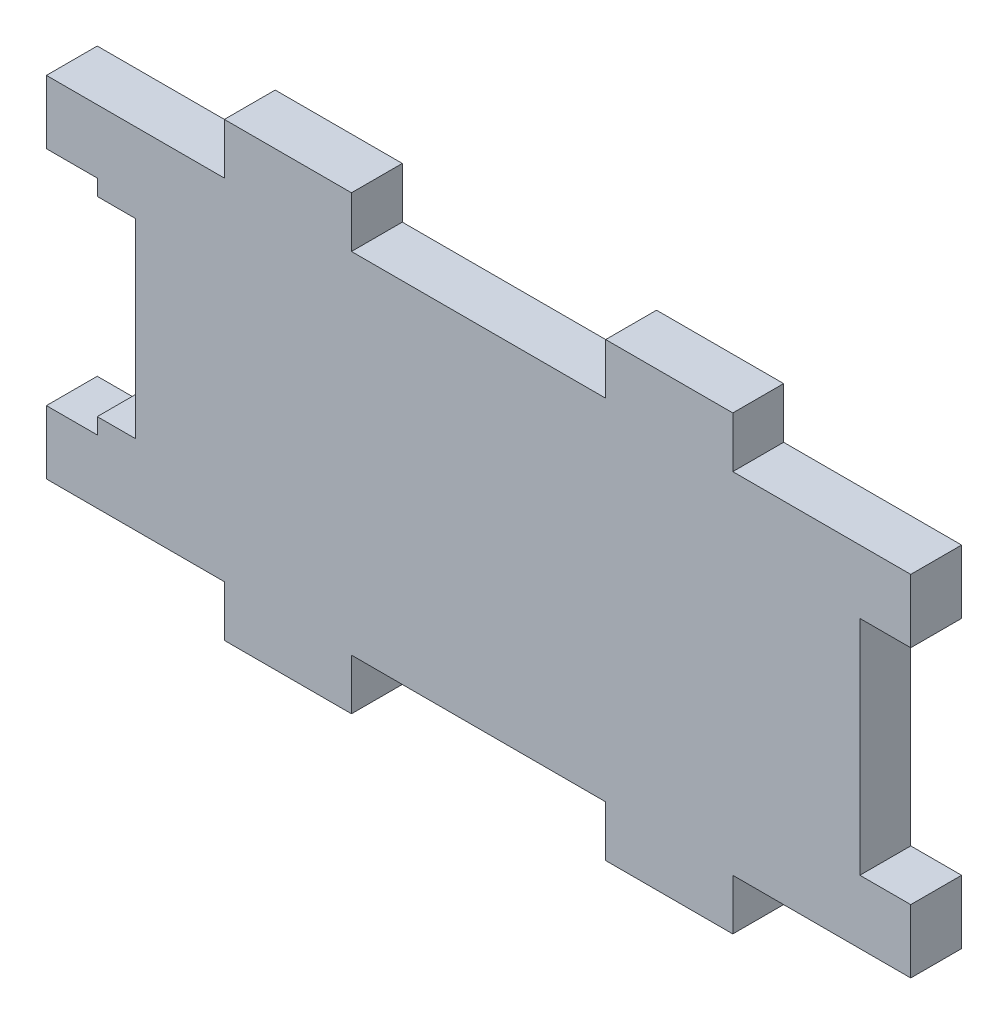
SolidWorks part; units mm, degrees
ref_plane "Front Plane" through (0, 0, 0) normal (0, 0, 1) x (1, 0, 0)
ref_plane "Top Plane" through (0, 0, 0) normal (0, 1, 0) x (1, 0, 0)
ref_plane "Right Plane" through (0, 0, 0) normal (1, 0, 0) x (0, 0, -1)
sketch "Sketch1" plane through (0, 0, 0) normal (0, 0, 1) x (1, 0, 0)
  line L1 (-60, 27.5) -> (60, 27.5)
  line L2 (-60, 27.5) -> (-60, -27.5)
  line L3 (-60, -27.5) -> (60, -27.5)
  line L4 (60, 27.5) -> (60, -27.5)
  point P4 (0, 27.5)
  point P6 (60, 0)
  dimension "D1" = 55
  dimension "D2" = 120
extrude "Boss-Extrude1" add sketch "Sketch1" along normal blind 8
sketch "Sketch2" plane through (0, 0, 8) normal (0, 0, 1) x (1, 0, 0)
  line L0 (-60, 27.5) -> (-60, -27.5) construction
  line L1 (-92.7508, 15) -> (-54, 15)
  line L2 (-92.7508, 15) -> (-92.7508, -15)
  line L3 (-92.7508, -15) -> (-54, -15)
  line L4 (-54, 15) -> (-54, -15)
  point P4 (-54, 0)
  point P7 (-60, 0)
  dimension "D1" = 30
  dimension "D2" = 6
extrude "Cut-Extrude1" cut sketch "Sketch2" against normal up to next
sketch "Sketch4" plane through (60, 0, 0) normal (1, 0, 0) x (0, 0, -1)
  line L1 (-8, 27.5) -> (0, 27.5)
  line L2 (-8, 27.5) -> (-8, 17.5)
  line L3 (-8, 17.5) -> (0, 17.5)
  line L4 (0, 27.5) -> (0, 17.5)
  line L5 (-8, 27.5) -> (0, 27.5) construction
  line L6 (0, -27.5) -> (0, 27.5) construction
  line L7 (-23.1797, 0) -> (12.6777, 0) construction
  line L8 (-8, -27.5) -> (-8, -17.5)
  line L9 (-8, -27.5) -> (0, -27.5)
  line L10 (0, -27.5) -> (0, -17.5)
  line L11 (-8, -17.5) -> (0, -17.5)
  dimension "D1" = 10
extrude "Boss-Extrude3" add sketch "Sketch4" along normal blind 8
sketch "Sketch6" plane through (0, -27.5, 0) normal (0, -1, 0) x (1, 0, 0)
  line L0 (0, 25.2996) -> (0, -15.5638) construction
  line L1 (-40, 8) -> (-20, 8)
  line L2 (-40, 8) -> (-40, 0)
  line L3 (-40, 0) -> (-20, 0)
  line L4 (-20, 8) -> (-20, 0)
  line L5 (20, 8) -> (20, 0)
  line L6 (40, 0) -> (20, 0)
  line L7 (40, 8) -> (40, 0)
  line L8 (40, 8) -> (20, 8)
  line L9 (-60, 8) -> (68, 8) construction
  line L10 (-60, 0) -> (68, 0) construction
  dimension "D1" = 20
  dimension "D2" = 40
extrude "Boss-Extrude4" add sketch "Sketch6" along normal blind 8
ref_plane "Plane1" through (0, 0, 0) normal (0, -1, 0) x (-1, 0, 0)
mirror "Mirror2" about plane through (0, 0, 0) normal (0, -1, 0) of "Boss-Extrude4"
ref_plane "Plane2" through (0, 0, 0) normal (-1, 0, 0) x (0, 0, 1)
mirror "Mirror3" about plane through (0, 0, 0) normal (-1, 0, 0) of "Boss-Extrude3"
